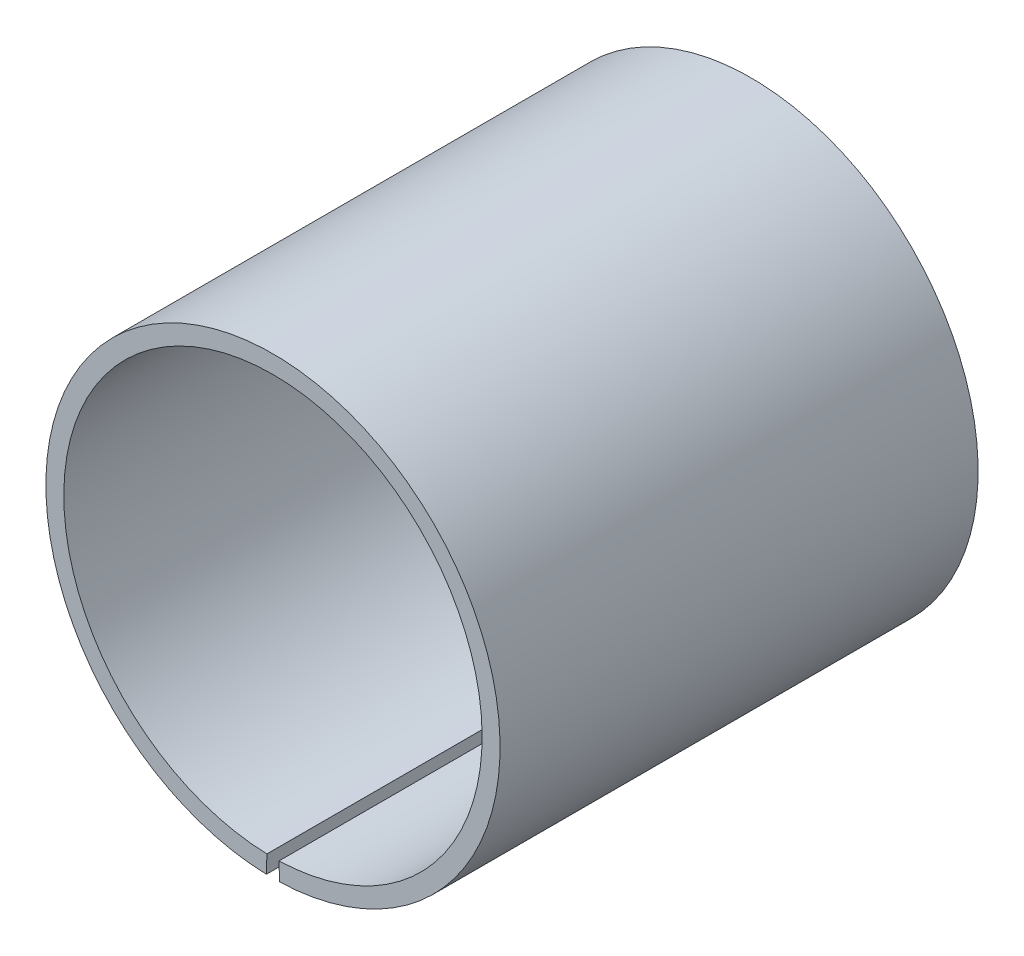
SolidWorks part; units mm, degrees
ref_plane "Front Plane" through (0, 0, 0) normal (0, 0, 1) x (1, 0, 0)
ref_plane "Top Plane" through (0, 0, 0) normal (0, 1, 0) x (1, 0, 0)
ref_plane "Right Plane" through (0, 0, 0) normal (1, 0, 0) x (0, 0, -1)
sketch "Sketch1" plane through (0, 0, 0) normal (0, 0, 1) x (1, 0, 0)
  line L0 (0, 0) -> (0, -25.2603) construction
  line L1 (-0.5068, -17.4927) -> (-0.5502, -18.992)
  line L3 (0.5502, -18.992) -> (0.5068, -17.4927)
  arc A0 (0.5068, -17.4927) -> (-0.5068, -17.4927) centre (0, 0) ccw
  arc A1 (0.5502, -18.992) -> (-0.5502, -18.992) centre (0, 0) ccw
  dimension "D1" = 38
  dimension "D2" = 1.5
extrude "Boss-Extrude1" add sketch "Sketch1" along normal blind 40
